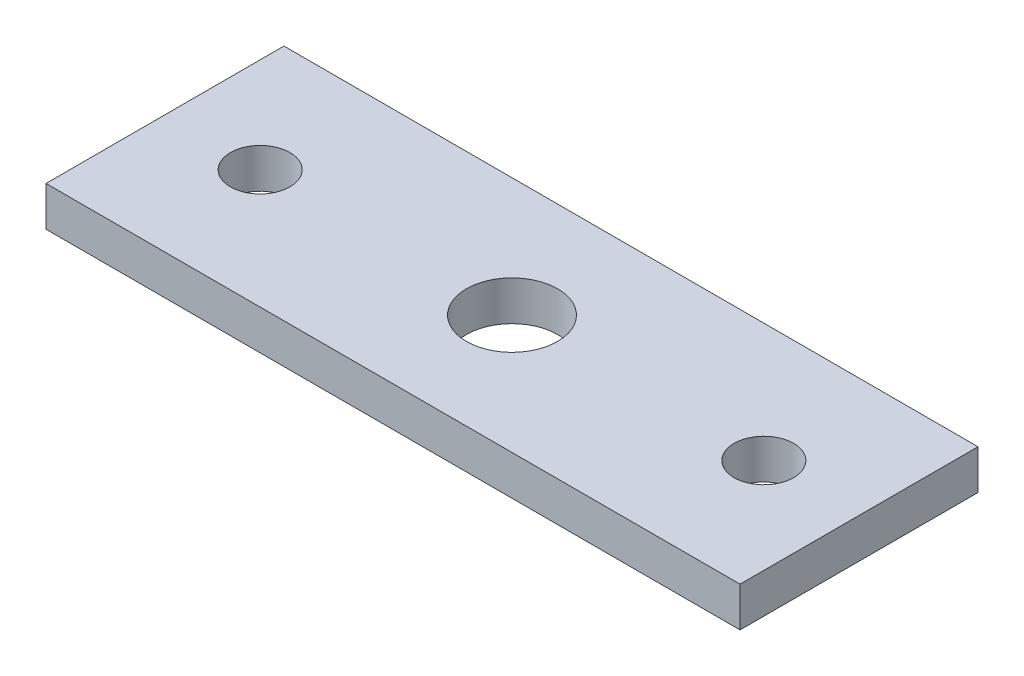
SolidWorks part; units mm, degrees
ref_plane "Front Plane" through (0, 0, 0) normal (0, 0, 1) x (1, 0, 0)
ref_plane "Top Plane" through (0, 0, 0) normal (0, 1, 0) x (1, 0, 0)
ref_plane "Right Plane" through (0, 0, 0) normal (1, 0, 0) x (0, 0, -1)
sketch "Sketch1" plane through (0, 0, 0) normal (0, 1, 0) x (1, 0, 0)
  line L0 (0, -6) -> (0, 6) construction
  line L1 (17.5, -6) -> (-17.5, -6)
  line L2 (17.5, -6) -> (17.5, 6)
  line L3 (17.5, 6) -> (-17.5, 6)
  line L4 (-17.5, -6) -> (-17.5, 6)
  line L5 (17.5, -6) -> (-17.5, 6) construction
  line L6 (17.5, 6) -> (-17.5, -6) construction
  circle A0 centre (0, 0) radius 2.3
  circle A1 centre (12.7, 0) radius 1.5
  circle A2 centre (-12.7, 0) radius 1.5
  point P0 (0, 0)
  point P14 (0, 0)
  dimension "D3" = 4.6
  dimension "D4" = 3
  dimension "D5" = 12.7
  dimension "D1" = 35
  dimension "D2" = 12
extrude "Boss-Extrude1" add sketch "Sketch1" along normal blind 2
